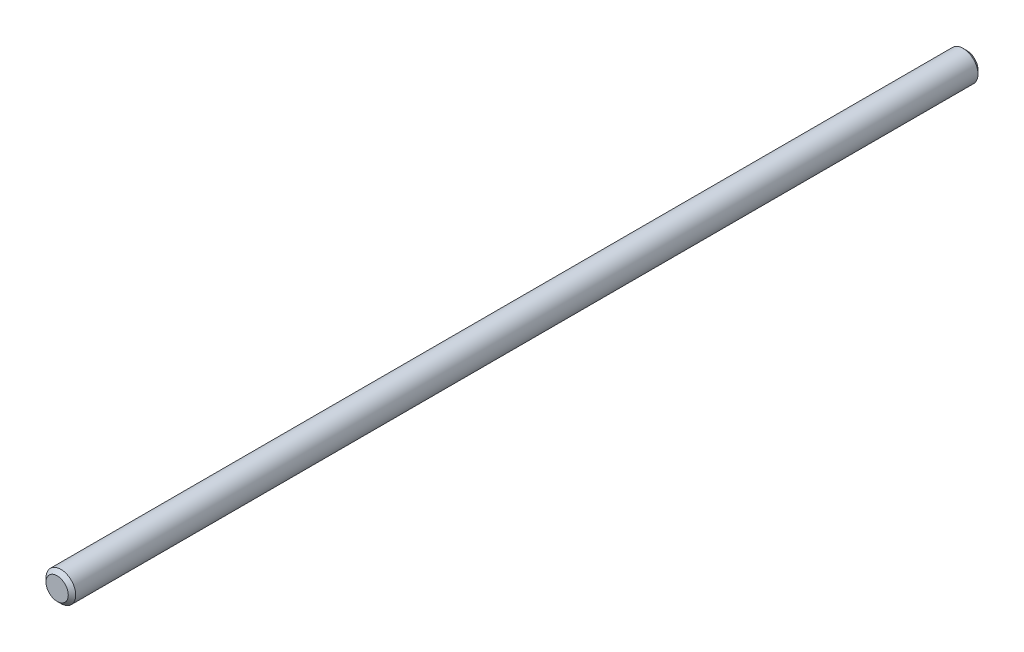
SolidWorks part; units mm, degrees
material "Slitina zinku AC41A Alloy, v odlitém stavu"
ref_plane "Přední rovina" through (0, 0, 0) normal (0, 0, 1) x (1, 0, 0)
ref_plane "Horní rovina" through (0, 0, 0) normal (0, 1, 0) x (1, 0, 0)
ref_plane "Pravá rovina" through (0, 0, 0) normal (1, 0, 0) x (0, 0, -1)
sketch "Skica1" plane through (0, 0, 0) normal (0, 0, 1) x (1, 0, 0)
  circle A0 centre (0, 0) radius 4
  dimension "D1" = 8
extrude "Přidat vysunutím1" add sketch "Skica1" along normal blind 245
chamfer "Zkosení1" distance 1 angle 45 2 edges at (4, 0, 0) (4, 0, 245)
